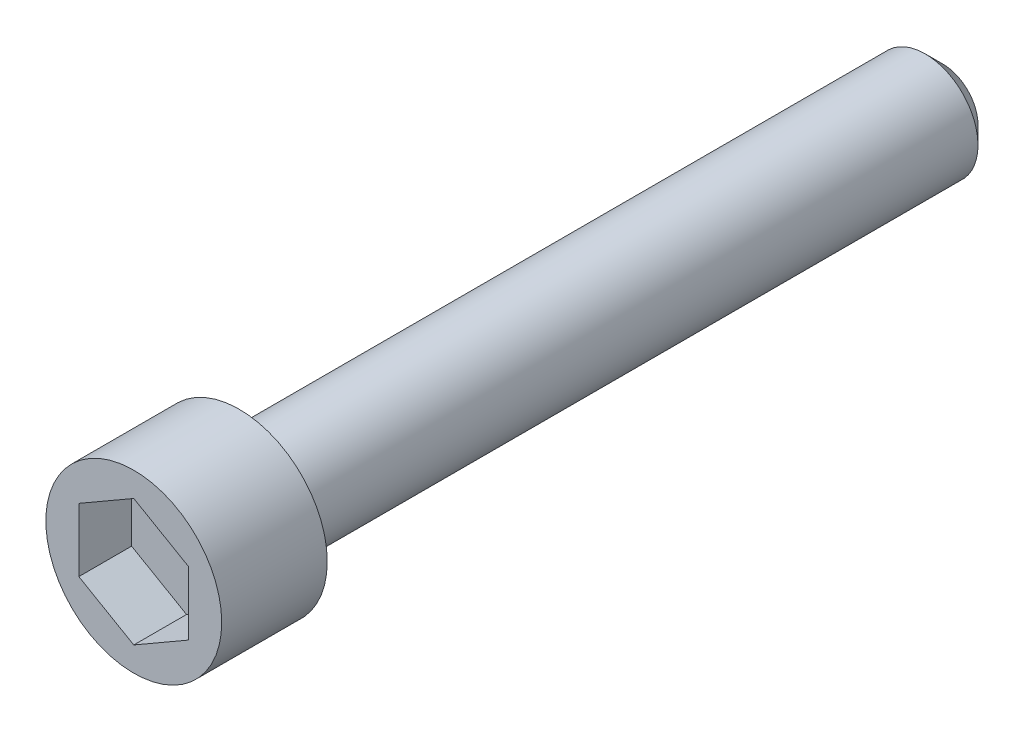
SolidWorks part; units mm, degrees
ref_plane "前视基准面" through (0, 0, 0) normal (0, 0, 1) x (1, 0, 0)
ref_plane "上视基准面" through (0, 0, 0) normal (0, 1, 0) x (1, 0, 0)
ref_plane "右视基准面" through (0, 0, 0) normal (1, 0, 0) x (0, 0, -1)
sketch "草图1" plane through (0, 0, 0) normal (0, 0, 1) x (1, 0, 0)
  circle A0 centre (0, 0) radius 1.5
extrude "凸台-拉伸1" add sketch "草图1" along normal blind 20
sketch "草图2" plane through (0, 0, 20) normal (0, 0, 1) x (1, 0, 0)
  circle A0 centre (0, 0) radius 2.5
extrude "凸台-拉伸2" add sketch "草图2" along normal blind 3
sketch "草图3" plane through (0, 0, 23) normal (0, 0, 1) x (1, 0, 0)
  line L1 (0, 1.8034) -> (-1.5618, 0.9017)
  line L2 (-1.5618, 0.9017) -> (-1.5618, -0.9017)
  line L3 (-1.5618, -0.9017) -> (0, -1.8034)
  line L4 (0, -1.8034) -> (1.5618, -0.9017)
  line L5 (1.5618, -0.9017) -> (1.5618, 0.9017)
  line L6 (1.5618, 0.9017) -> (0, 1.8034)
  circle A0 centre (0, 0) radius 1.5618 construction
extrude "切除-拉伸1" cut sketch "草图3" against normal blind 1.5
chamfer "倒角1" distance 0.5 angle 45 1 edges at (1.5, 0, 0)
